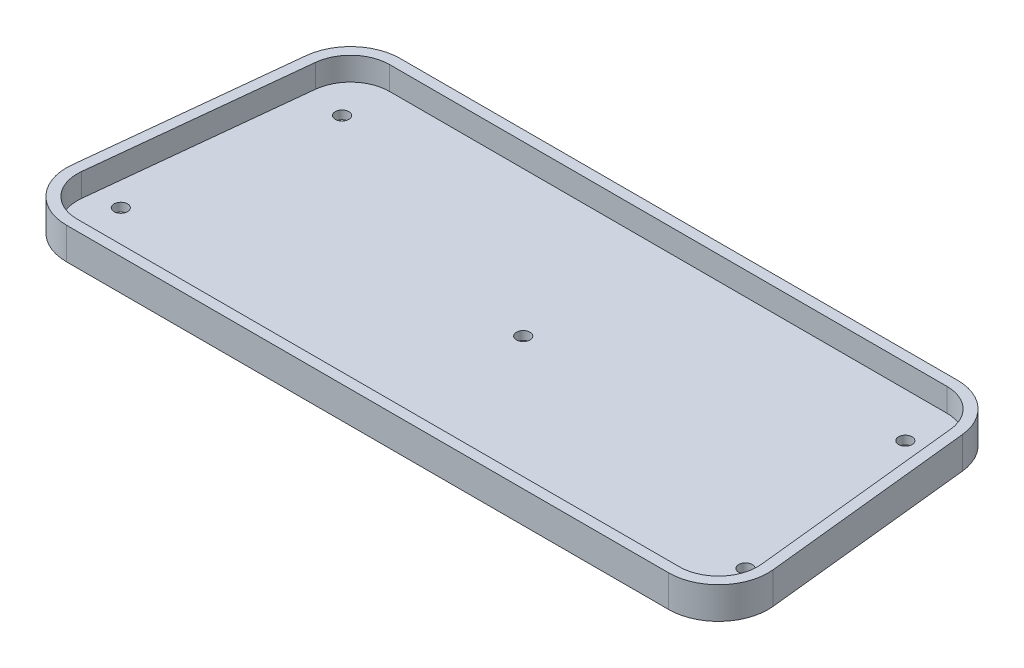
SolidWorks part; units mm, degrees
ref_plane "Front Plane" through (0, 0, 0) normal (0, 0, 1) x (1, 0, 0)
ref_plane "Top Plane" through (0, 0, 0) normal (0, 1, 0) x (1, 0, 0)
ref_plane "Right Plane" through (0, 0, 0) normal (1, 0, 0) x (0, 0, -1)
sketch "Sketch1" plane through (0, 0, 0) normal (0, 1, 0) x (1, 0, 0)
  line L24 (-101.1965, 62.2698) -> (-107.9313, -1.2302)
  line L25 (-96.2493, -14.2167) -> (84.3616, -14.2167)
  line L26 (96.0435, -1.2302) -> (89.3087, 62.2698)
  line L27 (77.6267, 72.7783) -> (-89.5145, 72.7783)
  line L28 (-101.1965, 62.2698) -> (-107.9313, -1.2302)
  line L29 (-96.2493, -14.2167) -> (84.3616, -14.2167)
  line L30 (96.0435, -1.2302) -> (89.3087, 62.2698)
  line L31 (77.6267, 72.7783) -> (-89.5145, 72.7783)
  arc A24 (-107.9313, -1.2302) -> (-96.2493, -14.2167) centre (-96.2493, -2.4692) ccw
  arc A25 (84.3616, -14.2167) -> (96.0435, -1.2302) centre (84.3616, -2.4692) ccw
  arc A26 (89.3087, 62.2698) -> (77.6267, 72.7783) centre (77.6267, 61.0308) ccw
  arc A27 (-89.5145, 72.7783) -> (-101.1965, 62.2698) centre (-89.5145, 61.0308) ccw
  arc A28 (-107.9313, -1.2302) -> (-96.2493, -14.2167) centre (-96.2493, -2.4692) ccw
  arc A29 (84.3616, -14.2167) -> (96.0435, -1.2302) centre (84.3616, -2.4692) ccw
  arc A30 (89.3087, 62.2698) -> (77.6267, 72.7783) centre (77.6267, 61.0308) ccw
  arc A31 (-89.5145, 72.7783) -> (-101.1965, 62.2698) centre (-89.5145, 61.0308) ccw
  circle A68 centre (78.5238, 59.4103) radius 2.032 construction
  circle A69 centre (87.7313, 2.2603) radius 2.032 construction
  circle A70 centre (-5.9439, 29.2808) radius 2.032 construction
  circle A71 centre (-99.6191, 2.2603) radius 2.032 construction
  circle A72 centre (-90.4116, 59.4103) radius 2.032 construction
  circle A73 centre (78.5238, 59.4103) radius 2.032
  circle A74 centre (87.7313, 2.2603) radius 2.032
  circle A75 centre (-5.9439, 29.2808) radius 2.032
  circle A76 centre (-99.6191, 2.2603) radius 2.032
  circle A77 centre (-90.4116, 59.4103) radius 2.032
  dimension "D1" = 1.5875
extrude "Boss-Extrude1" add sketch "Sketch1" along normal blind 2.54
sketch "Sketch4" plane through (0, 0, 0) normal (0, -1, 0) x (1, 0, 0)
  line L0 (77.6267, -72.7783) -> (-89.5145, -72.7783) construction
  line L1 (77.6267, -72.7783) -> (-89.5145, -72.7783)
  line L2 (-101.1965, -62.2698) -> (-107.9313, 1.2302) construction
  line L3 (-96.2493, 14.2167) -> (84.3616, 14.2167) construction
  line L4 (96.0435, 1.2302) -> (89.3087, -62.2698) construction
  line L5 (-101.1965, -62.2698) -> (-107.9313, 1.2302)
  line L6 (-96.2493, 14.2167) -> (84.3616, 14.2167)
  line L7 (96.0435, 1.2302) -> (89.3087, -62.2698)
  line L8 (99.2008, 0.8953) -> (92.466, -62.6047)
  line L9 (77.6267, -75.9533) -> (-89.5145, -75.9533)
  line L10 (-104.3538, -62.6047) -> (-111.0886, 0.8953)
  line L11 (-96.2493, 17.3917) -> (84.3616, 17.3917)
  arc A0 (-101.1965, -62.2698) -> (-89.5145, -72.7783) centre (-89.5145, -61.0308) ccw construction
  arc A1 (-101.1965, -62.2698) -> (-89.5145, -72.7783) centre (-89.5145, -61.0308) ccw
  arc A2 (-96.2493, 14.2167) -> (-107.9313, 1.2302) centre (-96.2493, 2.4692) ccw construction
  arc A3 (96.0435, 1.2302) -> (84.3616, 14.2167) centre (84.3616, 2.4692) ccw construction
  arc A4 (77.6267, -72.7783) -> (89.3087, -62.2698) centre (77.6267, -61.0308) ccw construction
  arc A5 (-96.2493, 14.2167) -> (-107.9313, 1.2302) centre (-96.2493, 2.4692) ccw
  arc A6 (96.0435, 1.2302) -> (84.3616, 14.2167) centre (84.3616, 2.4692) ccw
  arc A7 (77.6267, -72.7783) -> (89.3087, -62.2698) centre (77.6267, -61.0308) ccw
  arc A8 (77.6267, -75.9533) -> (92.466, -62.6047) centre (77.6267, -61.0308) ccw
  arc A9 (-104.3538, -62.6047) -> (-89.5145, -75.9533) centre (-89.5145, -61.0308) ccw
  arc A10 (-96.2493, 17.3917) -> (-111.0886, 0.8953) centre (-96.2493, 2.4692) ccw
  arc A11 (99.2008, 0.8953) -> (84.3616, 17.3917) centre (84.3616, 2.4692) ccw
  arc M9 (-101.1965, -62.2698) -> (-89.5145, -72.7783) centre (-89.5145, -61.0308) ccw
  line M10 (-89.5145, -72.7783) -> (77.6267, -72.7783)
  arc M11 (77.6267, -72.7783) -> (89.3087, -62.2698) centre (77.6267, -61.0308) ccw
  line M12 (89.3087, -62.2698) -> (96.0435, 1.2302)
  arc M13 (96.0435, 1.2302) -> (84.3616, 14.2167) centre (84.3616, 2.4692) ccw
  line M14 (84.3616, 14.2167) -> (-96.2493, 14.2167)
  arc M15 (-96.2493, 14.2167) -> (-107.9313, 1.2302) centre (-96.2493, 2.4692) ccw
  line M16 (-107.9313, 1.2302) -> (-101.1965, -62.2698)
  dimension "D1" = 3.175
  dimension "D2" = 3.175
extrude "Boss-Extrude2" add sketch "Sketch4" against normal blind 9.525 contours L8 A11 L11 A10 L10 A9 L9 A8 M9 M16 M15 M14 M13 M12 M11 M10
